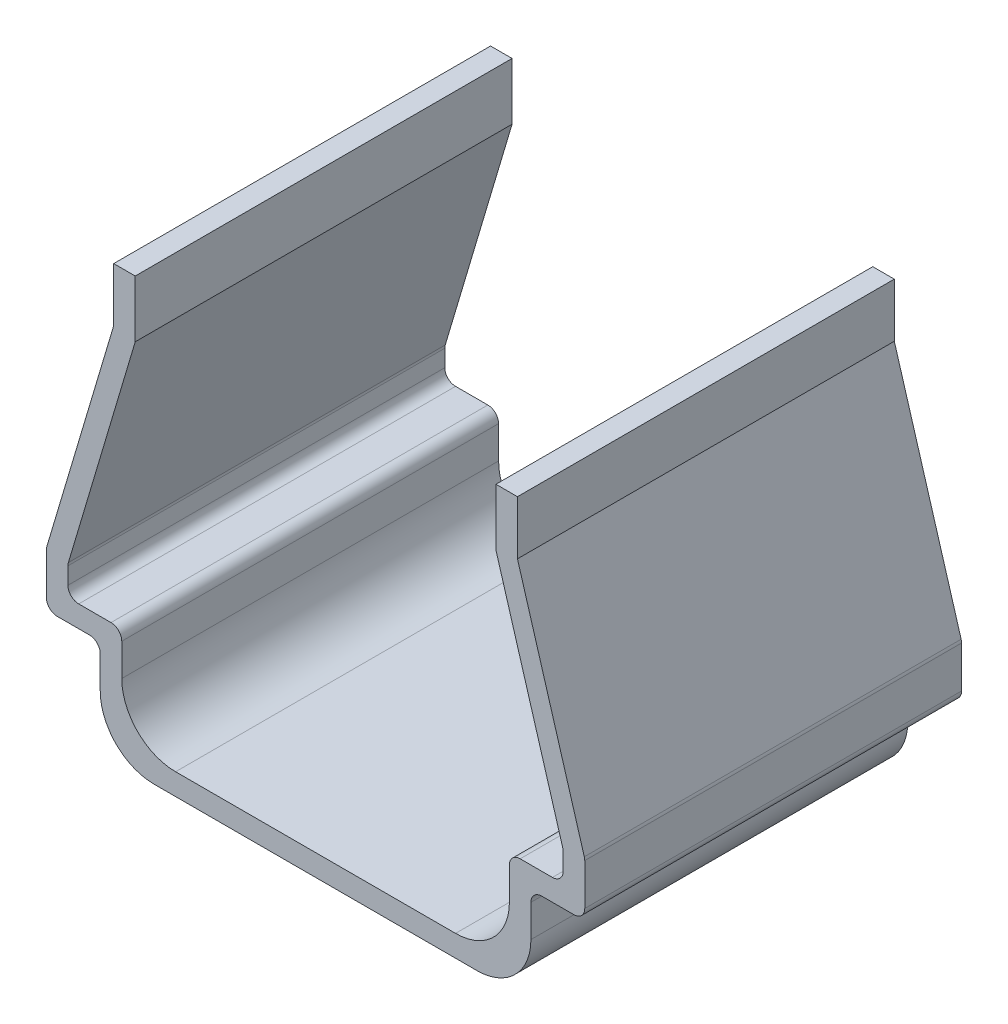
SolidWorks part; units mm, degrees
ref_plane "Front Plane" through (0, 0, 0) normal (0, 0, 1) x (1, 0, 0)
ref_plane "Top Plane" through (0, 0, 0) normal (0, 1, 0) x (1, 0, 0)
ref_plane "Right Plane" through (0, 0, 0) normal (1, 0, 0) x (0, 0, -1)
sketch "Sketch1" plane through (0, 0, 0) normal (0, 0, 1) x (1, 0, 0)
  line L0 (0, 0) -> (0, 7.1478) construction
  line L1 (4, 0) -> (-4, 0)
  line L2 (-4, 0) -> (-4, 1.8)
  line L3 (-4, 1.8) -> (-5, 1.8)
  line L4 (-5, 1.8) -> (-5, 2.8)
  line L5 (4, 0) -> (4, 1.8)
  line L6 (4, 1.8) -> (5, 1.8)
  line L7 (5, 1.8) -> (5, 2.8)
  line L8 (-5, 2.8) -> (-3.75, 7)
  line L9 (-3.75, 7) -> (-3.75, 8)
  line L10 (3.75, 7) -> (3.75, 8)
  line L11 (5, 2.8) -> (3.75, 7)
  dimension "D1" = 8
  dimension "D2" = 10
  dimension "D3" = 1.8
  dimension "D4" = 8
  dimension "D5" = 1
  dimension "D6" = 1
  dimension "D7" = 7.5
extrude "Extrude-Thin1" add sketch "Sketch1" along normal blind 7 thin
fillet "Fillet1" radius 1 4 edges at (3.6, 0.4, 3.5) (4, 0, 3.5) (-4, 0, 3.5) (-3.6, 0.4, 3.5)
fillet "Fillet2" radius 0.2 12 edges at (5, 2.8, 3.5) (4.6, 2.2, 3.5) (-4.6, 2.7417, 3.5) (-5, 2.8, 3.5) (-4.6, 2.2, 3.5) (5, 1.8, 3.5) (-5, 1.8, 3.5) (4.6, 2.7417, 3.5) (4, 1.8, 3.5) (3.6, 2.2, 3.5) (-4, 1.8, 3.5) (-3.6, 2.2, 3.5)
